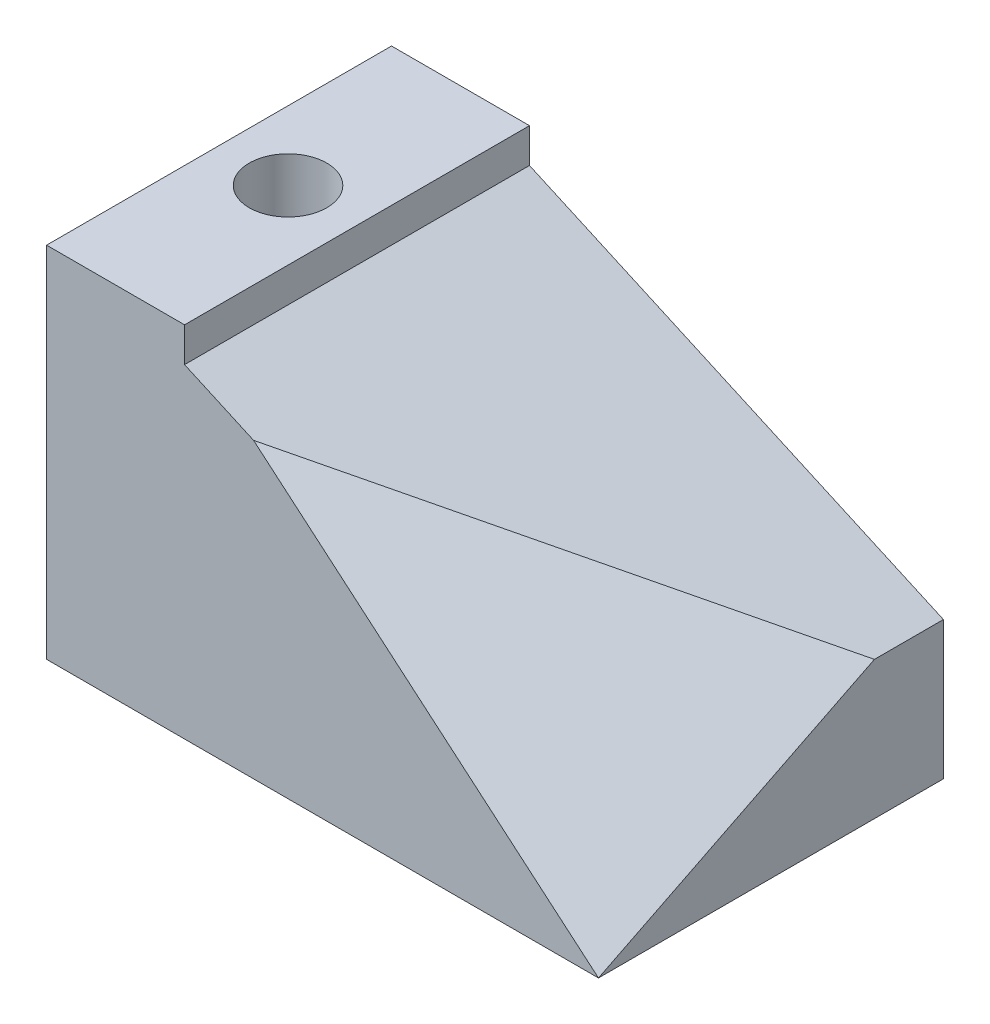
SolidWorks part; units mm, degrees
material "Alloy Steel"
ref_plane "Front Plane" through (0, 0, 0) normal (0, 0, 1) x (1, 0, 0)
ref_plane "Top Plane" through (0, 0, 0) normal (0, 1, 0) x (1, 0, 0)
ref_plane "Right Plane" through (0, 0, 0) normal (1, 0, 0) x (0, 0, -1)
sketch "Croquis1" plane through (0, 0, 0) normal (0, 0, 1) x (1, 0, 0)
  line L0 (0, 0) -> (0, 66.04)
  line L1 (0, 66.04) -> (25.4, 66.04)
  line L2 (25.4, 66.04) -> (25.4, 59.69)
  line L3 (25.4, 59.69) -> (101.6, 25.4)
  line L4 (101.6, 25.4) -> (101.6, 0)
  line L5 (101.6, 0) -> (0, 0)
  dimension "D1" = 6.35
  dimension "D2" = 25.4
  dimension "D3" = 101.6
  dimension "D4" = 66.04
  dimension "D5" = 25.4
extrude "Saliente-Extruir1" add sketch "Croquis1" along normal blind 63.5
sketch "Croquis2" plane through (0, 66.04, 0) normal (0, 1, 0) x (1, 0, 0)
  line L0 (0, -31.75) -> (25.4, -31.75) construction
  line L1 (0, -63.5) -> (0, 0) construction
  line L2 (25.4, -63.5) -> (25.4, 0) construction
  circle A0 centre (12.7, -31.75) radius 7.1374
  dimension "D1" = 14.2748
extrude "Cortar-Extruir1" cut sketch "Croquis2" against normal blind 38.1
sketch3d "Croquis3D1"
  line L0 (101.6, 0, 63.5) -> (101.6, 25.4, 12.7)
  line L1 (101.6, 25.4, 63.5) -> (101.6, 25.4, 0) construction
  line L2 (101.6, 0, 63.5) -> (38.1, 53.975, 63.5)
  line L3 (101.6, 25.4, 63.5) -> (25.4, 59.69, 63.5) construction
  line L4 (38.1, 53.975, 63.5) -> (101.6, 25.4, 12.7)
  line L5 (0, 66.04, 63.5) -> (0, 0, 63.5) construction
  dimension "D1" = 38.1
  dimension "D2" = 12.7
extrude "Cortar-Extruir2" cut sketch "Croquis3D1" along direction (-0.4104, -0.9119, 0) on the side against the normal blind 38.1
